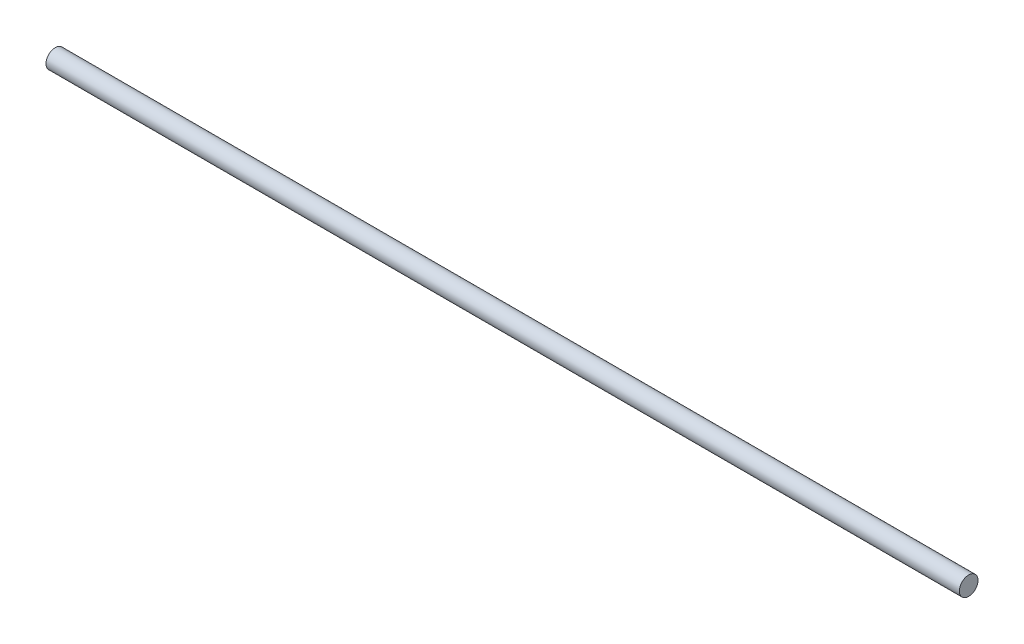
SolidWorks part; units mm, degrees
ref_plane "Front Plane" through (0, 0, 0) normal (0, 0, 1) x (1, 0, 0)
ref_plane "Top Plane" through (0, 0, 0) normal (0, 1, 0) x (1, 0, 0)
ref_plane "Right Plane" through (0, 0, 0) normal (1, 0, 0) x (0, 0, -1)
sketch "Sketch2" plane through (0, 0, 0) normal (1, 0, 0) x (0, 0, -1)
  circle A0 centre (0, 0) radius 0.8
extrude "Boss-Extrude1" add sketch "Sketch2" along normal blind 78.5
